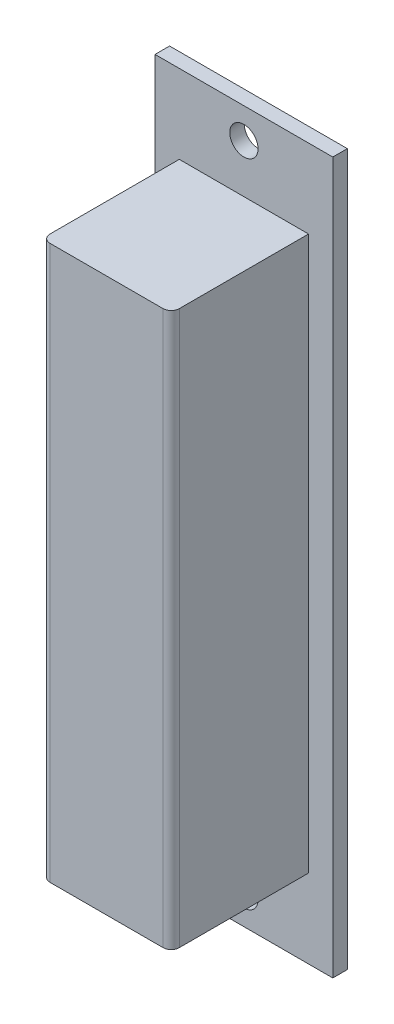
SolidWorks part; units mm, degrees
ref_plane "前视基准面" through (0, 0, 0) normal (0, 0, 1) x (1, 0, 0)
ref_plane "上视基准面" through (0, 0, 0) normal (0, 1, 0) x (1, 0, 0)
ref_plane "右视基准面" through (0, 0, 0) normal (1, 0, 0) x (0, 0, -1)
sketch "草图1" plane through (0, 0, 0) normal (0, 0, 1) x (1, 0, 0)
  line L0 (0, 48.626) -> (0, -83.7004) construction
  line L1 (-92.2698, 0) -> (95.8569, 0) construction
  line L2 (-11, 44) -> (11, 44)
  line L3 (-11, 44) -> (-11, -44)
  line L4 (-11, -44) -> (11, -44)
  line L5 (11, -44) -> (11, 44)
  circle A0 centre (0, 40.25) radius 1.75
  circle A1 centre (0, -40.25) radius 1.75
  dimension "D3" = 3.75
  dimension "D4" = 3.5
  dimension "D1" = 22
  dimension "D2" = 88
extrude "拉伸1" add sketch "草图1" along normal blind 1.8
sketch "草图2" plane through (0, 0, 1.8) normal (0, 0, 1) x (1, 0, 0)
  line L0 (0, 37.5456) -> (0, -35.199) construction
  line L1 (-34.3867, 0) -> (34.7477, 0) construction
  line L2 (-8, 34.25) -> (8, 34.25)
  line L3 (-8, 34.25) -> (-8, -34.25)
  line L4 (-8, -34.25) -> (8, -34.25)
  line L5 (8, -34.25) -> (8, 34.25)
  dimension "D1" = 16
  dimension "D2" = 68.5
extrude "拉伸2" add sketch "草图2" along normal blind 17
fillet "圆角1" radius 1 2 edges at (-8, 0, 18.8) (8, 0, 18.8)
